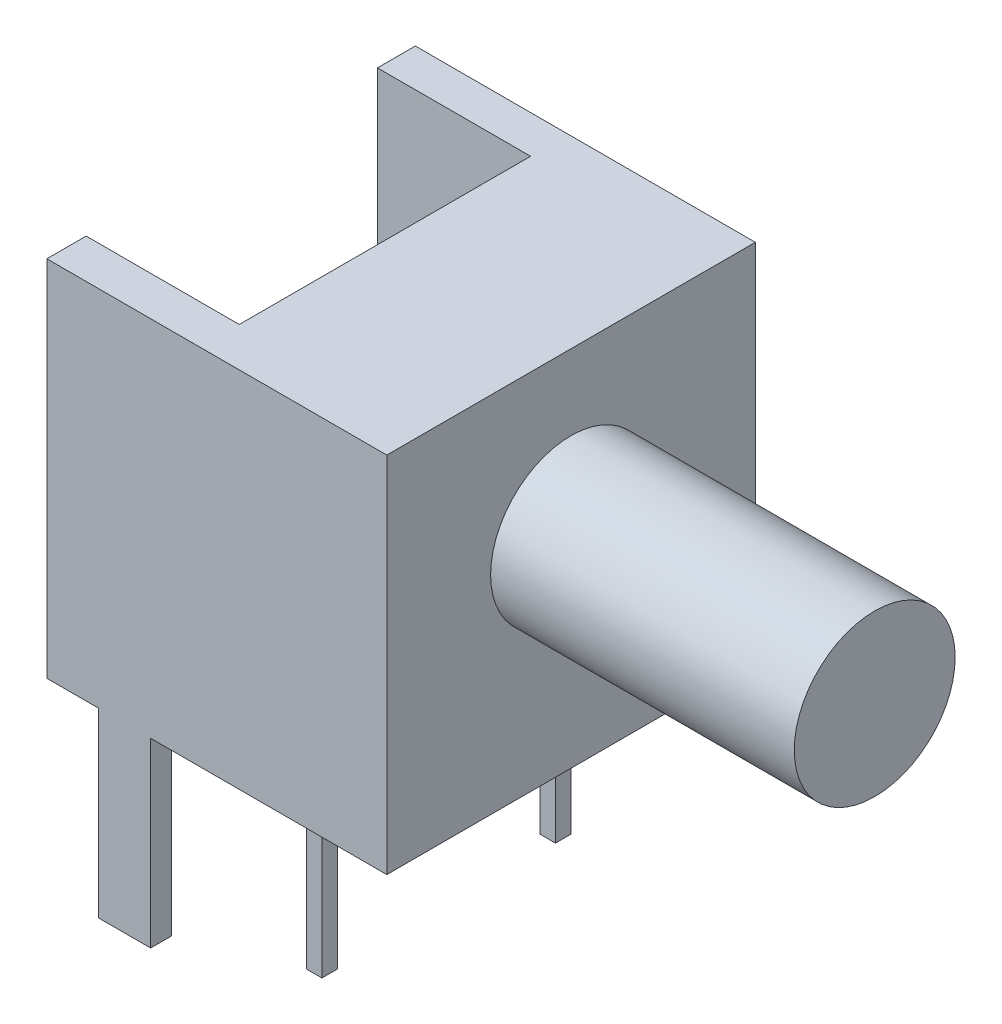
SolidWorks part; units mm, degrees
ref_plane "Front Plane" through (0, 0, 0) normal (0, 0, 1) x (1, 0, 0)
ref_plane "Top Plane" through (0, 0, 0) normal (0, 1, 0) x (1, 0, 0)
ref_plane "Right Plane" through (0, 0, 0) normal (1, 0, 0) x (0, 0, -1)
sketch "Sketch1" plane through (0, 0, 0) normal (1, 0, 0) x (0, 0, -1)
  line L1 (-3.55, -3.5) -> (3.55, -3.5)
  line L2 (-3.55, -3.5) -> (-3.55, 3.5)
  line L3 (-3.55, 3.5) -> (3.55, 3.5)
  line L4 (3.55, -3.5) -> (3.55, 3.5)
  line L5 (-3.55, -3.5) -> (3.55, 3.5) construction
  line L6 (-3.55, 3.5) -> (3.55, -3.5) construction
  point P0 (0, 0)
  dimension "D1" = 7.1
  dimension "D2" = 7
extrude "Boss-Extrude1" add sketch "Sketch1" against normal blind 6.55
sketch "Sketch2" plane through (0, -3.5, 0) normal (0, -1, 0) x (1, 0, 0)
  line L1 (-6.55, 3.55) -> (0, 3.55) construction
  line L9 (-2.7, 2.4) -> (-2.4, 2.4)
  line L10 (-5.55, 3.15) -> (-4.55, 3.15)
  line L11 (-5.55, 3.15) -> (-5.55, 3.55)
  line L12 (-5.55, 3.55) -> (-4.55, 3.55)
  line L13 (-4.55, 3.15) -> (-4.55, 3.55)
  line L14 (-5.55, 3.15) -> (-4.55, 3.55) construction
  line L15 (-5.55, 3.55) -> (-4.55, 3.15) construction
  line L16 (-2.7, 2.4) -> (-2.7, 2.1)
  line L17 (-2.7, 2.1) -> (-2.4, 2.1)
  line L18 (-2.4, 2.4) -> (-2.4, 2.1)
  line L19 (-2.7, 2.4) -> (-2.4, 2.1) construction
  line L20 (-2.7, 2.1) -> (-2.4, 2.4) construction
  point P9 (-5.05, 3.35)
  point P14 (-2.55, 2.25)
  dimension "D1" = 2.55
  dimension "D2" = 2.25
  dimension "D3" = 2.5
  dimension "D4" = 0.3
  dimension "D5" = 1
  dimension "D6" = 0.4
  dimension "D7" = 0.3
extrude "Boss-Extrude2" add sketch "Sketch2" along normal blind 3.5
mirror "Mirror1" about plane through (0, 0, 0) normal (0, 0, 1) of "Boss-Extrude2"
sketch "Sketch3" plane through (0, 3.5, 0) normal (0, 1, 0) x (1, 0, 0)
  line L0 (-6.55, 3.55) -> (-6.55, -3.55) construction
  line L1 (-6.55, 2.8201) -> (-3.6, 2.8201)
  line L2 (-6.55, 2.8201) -> (-6.55, -2.7924)
  line L3 (-6.55, -2.7924) -> (-3.6, -2.7924)
  line L4 (-3.6, 2.8201) -> (-3.6, -2.7924)
  line L5 (0, 3.55) -> (0, -3.55) construction
  dimension "D1" = 3.6
extrude "Cut-Extrude1" cut sketch "Sketch3" against normal through all
sketch "Sketch4" plane through (0, 0, 0) normal (1, 0, 0) x (0, 0, -1)
  line L0 (-3.55, -3.5) -> (3.55, -3.5) construction
  circle A0 centre (0, 0.5) radius 1.55
  dimension "D1" = 3.1
  dimension "D2" = 4
extrude "Boss-Extrude3" add sketch "Sketch4" along normal blind 5.85
